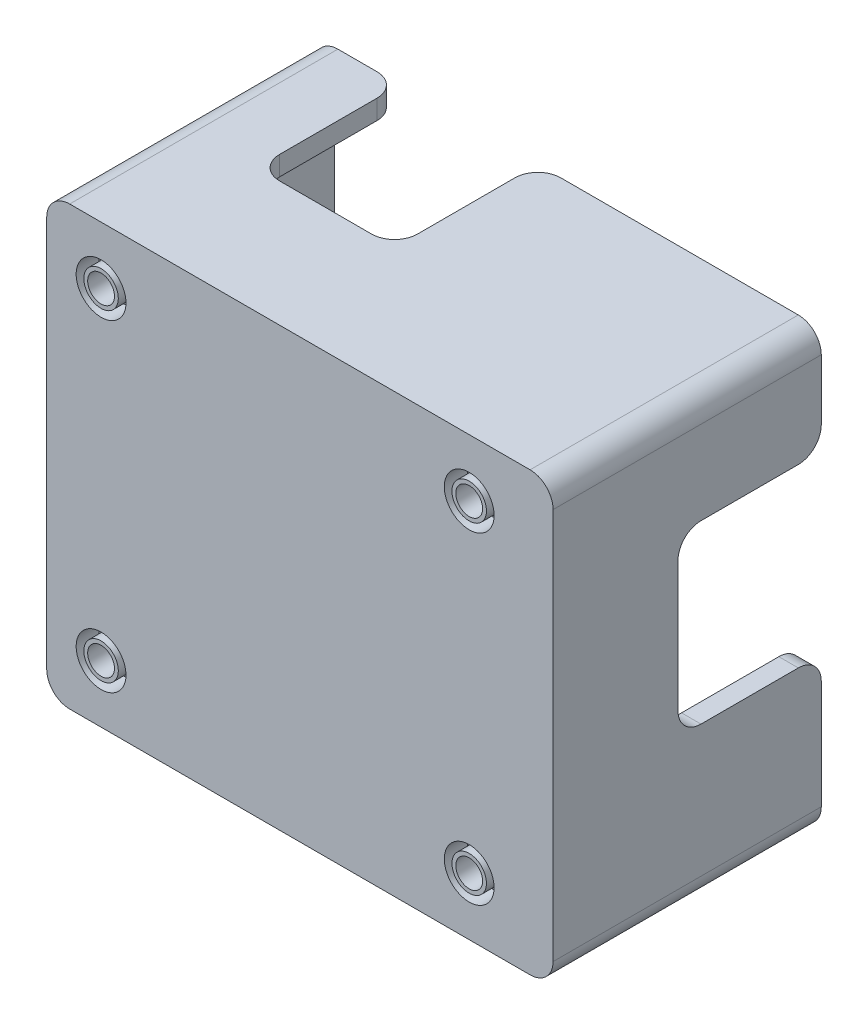
SolidWorks part; units mm, degrees
ref_plane "Front Plane" through (0, 0, 0) normal (0, 0, 1) x (1, 0, 0)
ref_plane "Top Plane" through (0, 0, 0) normal (0, 1, 0) x (1, 0, 0)
ref_plane "Right Plane" through (0, 0, 0) normal (1, 0, 0) x (0, 0, -1)
sketch "Sketch1" plane through (0, 0, 0) normal (0, 0, 1) x (1, 0, 0)
  line L0 (-180.74, 3.9892) -> (-180.74, -3.9892) construction
  line L1 (-211.24, 111.4335) -> (-150.24, 111.4335)
  line L2 (-211.24, 111.4335) -> (-211.24, 59.4335)
  line L3 (-211.24, 59.4335) -> (-150.24, 59.4335)
  line L4 (-150.24, 111.4335) -> (-150.24, 59.4335)
  line L5 (-180.74, 59.4335) -> (-180.74, 111.4335) construction
  line L6 (-211.24, 85.4335) -> (-150.24, 85.4335) construction
  line L7 (6.2759, 85.4335) -> (-6.2759, 85.4335) construction
  line L8 (-209.24, 109.4335) -> (-152.24, 109.4335) construction
  line L9 (-209.24, 61.4335) -> (-209.24, 109.4335) construction
  point P392 (-180.74, 85.4335)
  dimension "D1" = 2
  dimension "D2" = 2
extrude "Boss-Extrude1" add sketch "Sketch1" along normal blind 6
sketch "Sketch2" plane through (0, 0, 6) normal (0, 0, 1) x (1, 0, 0)
  line L4 (-211.24, 111.4335) -> (-211.24, 59.4335)
  line L5 (-211.24, 59.4335) -> (-150.24, 59.4335)
  line L6 (-150.24, 59.4335) -> (-150.24, 111.4335)
  line L7 (-150.24, 111.4335) -> (-211.24, 111.4335)
  line L8 (-211.24, 111.4335) -> (-211.24, 59.4335)
  line L9 (-211.24, 59.4335) -> (-150.24, 59.4335)
  line L10 (-150.24, 59.4335) -> (-150.24, 111.4335)
  line L11 (-150.24, 111.4335) -> (-211.24, 111.4335)
  line L16 (-213.78, 113.9735) -> (-213.78, 56.8935)
  line L17 (-213.78, 56.8935) -> (-147.7, 56.8935)
  line L18 (-147.7, 56.8935) -> (-147.7, 113.9735)
  line L19 (-147.7, 113.9735) -> (-213.78, 113.9735)
  line L20 (-213.78, 113.9735) -> (-213.78, 56.8935)
  line L21 (-213.78, 56.8935) -> (-147.7, 56.8935)
  line L22 (-147.7, 56.8935) -> (-147.7, 113.9735)
  line L23 (-147.7, 113.9735) -> (-213.78, 113.9735)
  dimension "D1" = 0
  dimension "D2" = 2.54
extrude "Boss-Extrude2" add sketch "Sketch2" against normal blind 35
sketch "Sketch3" plane through (0, 0, -29) normal (0, 0, -1) x (-1, 0, 0)
  line L0 (150.24, 111.4335) -> (211.24, 111.4335) construction
  line L1 (202.6875, 111.4335) -> (184.6875, 111.4335)
  line L2 (202.6875, 111.4335) -> (202.6875, 113.9735)
  line L3 (202.6875, 113.9735) -> (184.6875, 113.9735)
  line L4 (184.6875, 111.4335) -> (184.6875, 113.9735)
  line L5 (147.7, 113.9735) -> (213.78, 113.9735) construction
  line L6 (184.6875, 64.3985) -> (184.6875, 106.3985) construction
  line L7 (202.6875, 106.3985) -> (202.6875, 64.3985) construction
  line L8 (150.24, 59.4335) -> (150.24, 111.4335) construction
  line L9 (150.24, 100.0658) -> (147.7, 100.0658)
  line L10 (150.24, 100.0658) -> (150.24, 77.084)
  line L11 (150.24, 77.084) -> (147.7, 77.084)
  line L12 (147.7, 100.0658) -> (147.7, 77.084)
  line L13 (147.7, 56.8935) -> (147.7, 113.9735) construction
  line L14 (147.207, 98.0658) -> (150.8555, 98.0658) construction
  line L15 (151.24, 79.084) -> (158.8923, 79.084) construction
  dimension "D1" = 2
  dimension "D2" = 2
extrude "Cut-Extrude1" cut sketch "Sketch3" against normal offset from surface (18.7 mm away) 1
fillet "Fillet1" radius 3 16 edges at (-148.97, 77.084, -29) (-148.97, 100.0658, -29) (-184.6875, 112.7035, -29) (-202.6875, 112.7035, -29) (-184.6875, 112.7035, -10.3) (-202.6875, 112.7035, -10.3) (-148.97, 77.084, -10.3) (-148.97, 100.0658, -10.3) (-147.7, 113.9735, -11.5) (-150.24, 111.4335, -14.5) (-150.24, 59.4335, -14.5) (-147.7, 56.8935, -11.5) (-211.24, 59.4335, -14.5) (-213.78, 56.8935, -11.5) (-213.78, 113.9735, -11.5) (-211.24, 111.4335, -14.5)
sketch "Sketch4" plane through (0, 0, 0) normal (0, 0, -1) x (-1, 0, 0)
  circle A26 centre (206.6855, 64.3985) radius 1.75
  circle A27 centre (206.6855, 64.3985) radius 1.75
  circle A29 centre (158.6455, 64.3985) radius 1.75
  circle A30 centre (158.6455, 64.3985) radius 1.75
  circle A36 centre (206.6855, 106.4685) radius 1.75
  circle A37 centre (206.6855, 106.4685) radius 1.75
  circle A43 centre (158.6455, 106.4685) radius 1.75
  circle A44 centre (158.6455, 106.4685) radius 1.75
  dimension "D2" = 0.5
  dimension "D3" = 0.5
  dimension "D4" = 0.5
  dimension "D5" = 0.5
extrude "Cut-Extrude3" cut sketch "Sketch4" against normal through all
sketch "Sketch5" plane through (0, 0, 6) normal (0, 0, 1) x (1, 0, 0)
  circle A6 centre (-206.6855, 64.3985) radius 3.25
  circle A7 centre (-206.6855, 64.3985) radius 3.25
  circle A9 centre (-206.6855, 106.4685) radius 3.25
  circle A10 centre (-206.6855, 106.4685) radius 3.25
  circle A12 centre (-158.6455, 64.3985) radius 3.25
  circle A13 centre (-158.6455, 64.3985) radius 3.25
  circle A15 centre (-158.6455, 106.4685) radius 3.25
  circle A16 centre (-158.6455, 106.4685) radius 3.25
  dimension "D1" = 1.5
  dimension "D2" = 1.5
  dimension "D3" = 1.5
  dimension "D4" = 1.5
extrude "Cut-Extrude4" cut sketch "Sketch5" against normal blind 3
sketch "Sketch6" plane through (0, 0, 6) normal (0, 0, 1) x (1, 0, 0)
  circle A2 centre (-158.6455, 64.3985) radius 2.25
  circle A3 centre (-158.6455, 64.3985) radius 2.25
  circle A10 centre (-206.6855, 106.4685) radius 2.25
  circle A11 centre (-206.6855, 106.4685) radius 2.25
  circle A13 centre (-158.6455, 106.4685) radius 2.25
  circle A14 centre (-158.6455, 106.4685) radius 2.25
  circle A20 centre (-206.6855, 64.3985) radius 1.75 construction
  circle A21 centre (-206.6855, 64.3985) radius 2.25
  circle A22 centre (-206.6855, 64.3985) radius 2.25
  circle A23 centre (-206.6855, 64.3985) radius 1.75
  circle A24 centre (-158.6455, 64.3985) radius 1.75 construction
  circle A25 centre (-158.6455, 106.4685) radius 1.75 construction
  circle A26 centre (-206.6855, 106.4685) radius 1.75 construction
  circle A27 centre (-158.6455, 64.3985) radius 1.75
  circle A28 centre (-158.6455, 106.4685) radius 1.75
  circle A29 centre (-206.6855, 106.4685) radius 1.75
  dimension "D1" = 0.5
  dimension "D2" = 0.5
  dimension "D3" = 0.5
  dimension "D4" = 0.5
extrude "Boss-Extrude3" add sketch "Sketch6" against normal offset from surface (2.75 mm away) 0.25 up to face at (-155.3955, 64.3985, 3)
equation "\"1mmm\"=33.94"
